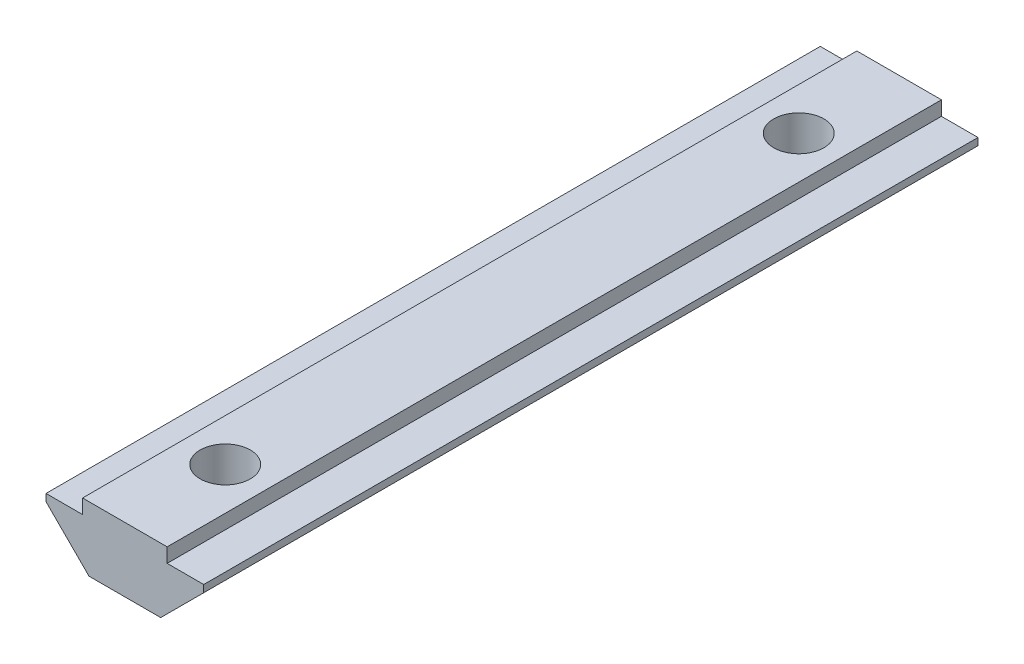
SolidWorks part; units mm, degrees
ref_plane "Plan de face" through (0, 0, 0) normal (0, 0, 1) x (1, 0, 0)
ref_plane "Plan de dessus" through (0, 0, 0) normal (0, 1, 0) x (1, 0, 0)
ref_plane "Plan de droite" through (0, 0, 0) normal (1, 0, 0) x (0, 0, -1)
sketch "Esquisse1" plane through (0, 0, 0) normal (0, 0, 1) x (1, 0, 0)
  line L0 (-2.5, 0) -> (2.5, 0)
  line L1 (2.5, 0) -> (5.5, 3)
  line L2 (5.5, 3) -> (5.5, 3.5)
  line L3 (5.5, 3.5) -> (2.95, 3.5)
  line L4 (2.95, 3.5) -> (2.95, 4.5)
  line L5 (2.95, 4.5) -> (-2.95, 4.5)
  line L6 (0, 4.5) -> (0, 0) construction
  line L7 (-2.95, 3.5) -> (-2.95, 4.5)
  line L8 (-5.5, 3.5) -> (-2.95, 3.5)
  line L9 (-5.5, 3) -> (-5.5, 3.5)
  line L10 (-2.5, 0) -> (-5.5, 3)
  dimension "D1" = 11
  dimension "D2" = 3.5
  dimension "D3" = 5.9
  dimension "D4" = 1
  dimension "D5" = 135
  dimension "D6" = 3
extrude "Boss.-Extru.1" add sketch "Esquisse1" along normal blind 54
sketch "Esquisse2" plane through (0, 4.5, 0) normal (0, 1, 0) x (1, 0, 0)
  line L0 (0, -54) -> (0, 0) construction
  line L1 (2.95, -54) -> (-2.95, -54) construction
  line L2 (0, -27) -> (-5.5, -27) construction
  line L3 (-5.5, -54) -> (-5.5, 0) construction
  circle A0 centre (0, -7) radius 1.75
  circle A1 centre (0, -47) radius 1.75
  dimension "D1" = 40
  dimension "D2" = 3.5
extrude "Enlèv. mat.-Extru.1" cut sketch "Esquisse2" against normal through all
